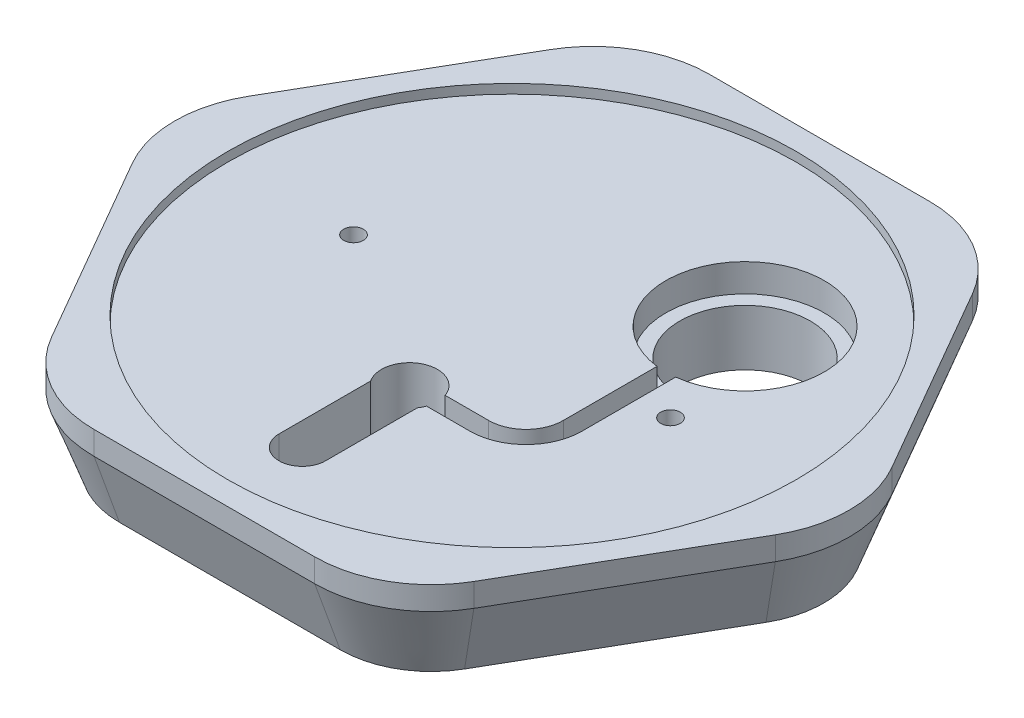
SolidWorks part; units mm, degrees
ref_plane "Front Plane" through (0, 0, 0) normal (0, 0, 1) x (1, 0, 0)
ref_plane "Top Plane" through (0, 0, 0) normal (0, 1, 0) x (1, 0, 0)
ref_plane "Right Plane" through (0, 0, 0) normal (1, 0, 0) x (0, 0, -1)
sketch "Sketch1" plane through (0, 0, 0) normal (0, 1, 0) x (1, 0, 0)
  line L1 (68.9934, 12.5) -> (45.322, 53.5)
  line L2 (23.6714, 66) -> (-23.6714, 66)
  line L3 (-45.322, 53.5) -> (-68.9934, 12.5)
  line L4 (-68.9934, -12.5) -> (-45.322, -53.5)
  line L5 (-23.6714, -66) -> (23.6714, -66)
  line L6 (45.322, -53.5) -> (68.9934, -12.5)
  circle A0 centre (0, 0) radius 66 construction
  arc A1 (-68.9934, 12.5) -> (-68.9934, -12.5) centre (-47.3427, 0) ccw
  arc A2 (-45.322, -53.5) -> (-23.6714, -66) centre (-23.6714, -41) ccw
  arc A3 (23.6714, -66) -> (45.322, -53.5) centre (23.6714, -41) ccw
  arc A4 (68.9934, -12.5) -> (68.9934, 12.5) centre (47.3427, 0) ccw
  arc A5 (45.322, 53.5) -> (23.6714, 66) centre (23.6714, 41) ccw
  arc A6 (-23.6714, 66) -> (-45.322, 53.5) centre (-23.6714, 41) ccw
  dimension "D2" = 25
  dimension "D1" = 132
extrude "Boss-Extrude1" add sketch "Sketch1" along normal blind 5
sketch "Sketch2" plane through (0, 0, 0) normal (0, -1, 0) x (1, 0, 0)
  line L6 (-68.9934, -12.5) -> (-45.322, -53.5)
  line L7 (-23.6714, -66) -> (23.6714, -66)
  line L8 (45.322, -53.5) -> (68.9934, -12.5)
  line L9 (68.9934, 12.5) -> (45.322, 53.5)
  line L10 (23.6714, 66) -> (-23.6714, 66)
  line L11 (-45.322, 53.5) -> (-68.9934, 12.5)
  line L12 (-68.9934, -12.5) -> (-45.322, -53.5)
  line L13 (-23.6714, -66) -> (23.6714, -66)
  line L14 (45.322, -53.5) -> (68.9934, -12.5)
  line L15 (68.9934, 12.5) -> (45.322, 53.5)
  line L16 (23.6714, 66) -> (-23.6714, 66)
  line L17 (-45.322, 53.5) -> (-68.9934, 12.5)
  arc A6 (-68.9934, 12.5) -> (-68.9934, -12.5) centre (-47.3427, 0) ccw
  arc A7 (-45.322, -53.5) -> (-23.6714, -66) centre (-23.6714, -41) ccw
  arc A8 (23.6714, -66) -> (45.322, -53.5) centre (23.6714, -41) ccw
  arc A9 (68.9934, -12.5) -> (68.9934, 12.5) centre (47.3427, 0) ccw
  arc A10 (45.322, 53.5) -> (23.6714, 66) centre (23.6714, 41) ccw
  arc A11 (-23.6714, 66) -> (-45.322, 53.5) centre (-23.6714, 41) ccw
  arc A12 (-68.9934, 12.5) -> (-68.9934, -12.5) centre (-47.3427, 0) ccw
  arc A13 (-45.322, -53.5) -> (-23.6714, -66) centre (-23.6714, -41) ccw
  arc A14 (23.6714, -66) -> (45.322, -53.5) centre (23.6714, -41) ccw
  arc A15 (68.9934, -12.5) -> (68.9934, 12.5) centre (47.3427, 0) ccw
  arc A16 (45.322, 53.5) -> (23.6714, 66) centre (23.6714, 41) ccw
  arc A17 (-23.6714, 66) -> (-45.322, 53.5) centre (-23.6714, 41) ccw
  dimension "D1" = 0
extrude "Boss-Extrude2" add sketch "Sketch2" along normal blind 15 draft 20
sketch "Sketch3" plane through (0, 5, 0) normal (0, 1, 0) x (1, 0, 0)
  circle A0 centre (0, 0) radius 61
  dimension "D1" = 122
extrude "Cut-Extrude1" cut sketch "Sketch3" against normal blind 2
sketch "Sketch4" plane through (0, 3, 0) normal (0, 1, 0) x (1, 0, 0)
  circle A0 centre (25, 25) radius 17
  dimension "D2" = 34
  dimension "D1" = 25
  dimension "D3" = 25
extrude "Cut-Extrude2" cut sketch "Sketch4" against normal blind 6
sketch "Sketch7" plane through (0, -3, 0) normal (0, 1, 0) x (1, 0, 0)
  circle A0 centre (25, 25) radius 17 construction
  circle A1 centre (25, 25) radius 17 construction
  circle A2 centre (25, 25) radius 14
  dimension "D1" = 28
extrude "Cut-Extrude3" cut sketch "Sketch7" against normal up to next
sketch "Sketch8" plane through (0, -15, 0) normal (0, -1, 0) x (-1, 0, 0)
  circle A0 centre (0, 0) radius 12.7
  dimension "D1" = 25.4
extrude "Cut-Extrude4" cut sketch "Sketch8" against normal offset from surface (16 mm away) 2 up to face at (25, 3, -8)
sketch "Sketch9" plane through (0, 3, 0) normal (0, 1, 0) x (1, 0, 0)
  circle A0 centre (34, 0) radius 2.1
  circle A1 centre (-34, 0) radius 2.1
  dimension "D1" = 4.2
  dimension "D2" = 4.2
  dimension "D3" = 34
  dimension "D4" = 34
extrude "Cut-Extrude5" cut sketch "Sketch9" against normal blind 20
sketch "Sketch12" plane through (0, 0, -66) normal (0, 0, -1) x (-1, 0, 0)
  circle A0 centre (0, -7) radius 4.1
  dimension "D1" = 8.2
  dimension "D2" = 7
extrude "Cut-Extrude7" cut sketch "Sketch12" against normal blind 60
sketch "Sketch13" plane through (0, 0, -66) normal (0, 0, -1) x (-1, 0, 0)
  circle A2 centre (0, -7) radius 7.1
  circle A5 centre (0, -7) radius 4.1 construction
  circle A6 centre (0, -7) radius 4.1
  dimension "D1" = 14.2
extrude "Cut-Extrude8" cut sketch "Sketch13" against normal blind 15 contours A2
sketch "Sketch14" plane through (0, -15, 0) normal (0, -1, 0) x (-1, 0, 0)
  line L0 (0, 0) -> (0, 25) construction
  line L1 (-7.25, 28.5) -> (7.25, 28.5)
  line L2 (-7.25, 28.5) -> (-7.25, 21.5)
  line L3 (-7.25, 21.5) -> (7.25, 21.5)
  line L4 (7.25, 28.5) -> (7.25, 21.5)
  line L5 (-7.25, 28.5) -> (7.25, 21.5) construction
  line L6 (-7.25, 21.5) -> (7.25, 28.5) construction
  point P0 (0, 25)
  dimension "D1" = 14.5
  dimension "D2" = 7
  dimension "D3" = 25
extrude "Cut-Extrude9" cut sketch "Sketch14" against normal blind 16
sketch "Sketch15" plane through (0, -15, 0) normal (0, -1, 0) x (1, 0, 0)
  line L1 (-34, 4.1569) -> (-37.6, 2.0785)
  line L2 (-37.6, 2.0785) -> (-37.6, -2.0785)
  line L3 (-37.6, -2.0785) -> (-34, -4.1569)
  line L4 (-34, -4.1569) -> (-30.4, -2.0785)
  line L5 (-30.4, -2.0785) -> (-30.4, 2.0785)
  line L6 (-30.4, 2.0785) -> (-34, 4.1569)
  line L7 (34, 4.1569) -> (30.4, 2.0785)
  line L8 (30.4, 2.0785) -> (30.4, -2.0785)
  line L9 (30.4, -2.0785) -> (34, -4.1569)
  line L10 (34, -4.1569) -> (37.6, -2.0785)
  line L11 (37.6, -2.0785) -> (37.6, 2.0785)
  line L12 (37.6, 2.0785) -> (34, 4.1569)
  circle A0 centre (-34, 0) radius 2.1 construction
  circle A1 centre (34, 0) radius 2.1 construction
  circle A2 centre (-34, 0) radius 2.1
  circle A3 centre (34, 0) radius 2.1
  circle A6 centre (-34, 0) radius 3.6 construction
  circle A7 centre (34, 0) radius 3.6 construction
  dimension "D1" = 7.2
  dimension "D2" = 7.2
extrude "Cut-Extrude10" cut sketch "Sketch15" against normal blind 5
sketch "Sketch16" plane through (0, 3, 0) normal (0, 1, 0) x (1, 0, 0)
  circle A0 centre (0, -22) radius 6
  dimension "D2" = 12
  dimension "D1" = 22
extrude "Cut-Extrude11" cut sketch "Sketch16" against normal up to next
sketch "Sketch17" plane through (0, 3, 0) normal (0, 1, 0) x (1, 0, 0)
  line L0 (25, 25) -> (25, -12)
  line L1 (15, -22) -> (0, -22)
  line L2 (23, 25) -> (23, -12)
  line L3 (15, -20) -> (0, -20)
  line L4 (27, 25) -> (27, -12)
  line L5 (15, -24) -> (0, -24)
  line L6 (23, 25) -> (27, 25)
  line L7 (0, -24) -> (0, -20)
  circle A0 centre (25, 25) radius 17 construction
  circle A1 centre (25, 25) radius 17
  circle A2 centre (0, -22) radius 6 construction
  circle A3 centre (0, -22) radius 6
  arc A4 (25, -12) -> (15, -22) centre (15, -12) cw
  arc A5 (23, -12) -> (15, -20) centre (15, -12) cw
  arc A6 (27, -12) -> (15, -24) centre (15, -12) cw
  circle M6 centre (0, -22) radius 6
  circle M10 centre (25, 25) radius 17
  dimension "D1" = 10
  dimension "D2" = 2
  dimension "D3" = 2
extrude "Cut-Extrude12" cut sketch "Sketch17" against normal blind 12 contours L2 A5 L3 L1 A4 L0 M6 M10 | A6 L4 L0 A4 L1 L5 M10 M6 | L6 L2 L0 M10 | L6 L0 L4 M10
sketch "Sketch18" plane through (0, 3, 0) normal (0, 1, 0) x (1, 0, 0)
  line L0 (0, -25) -> (0, -45) construction
  line L1 (5, -25) -> (5, -45)
  line L2 (-5, -25) -> (-5, -45)
  arc A0 (5, -25) -> (-5, -25) centre (0, -25) ccw
  arc A1 (-5, -45) -> (5, -45) centre (0, -45) ccw
  point P2 (0, -35)
  dimension "D1" = 5
  dimension "D2" = 45
  dimension "D3" = 20
extrude "Cut-Extrude13" cut sketch "Sketch18" against normal blind 10
